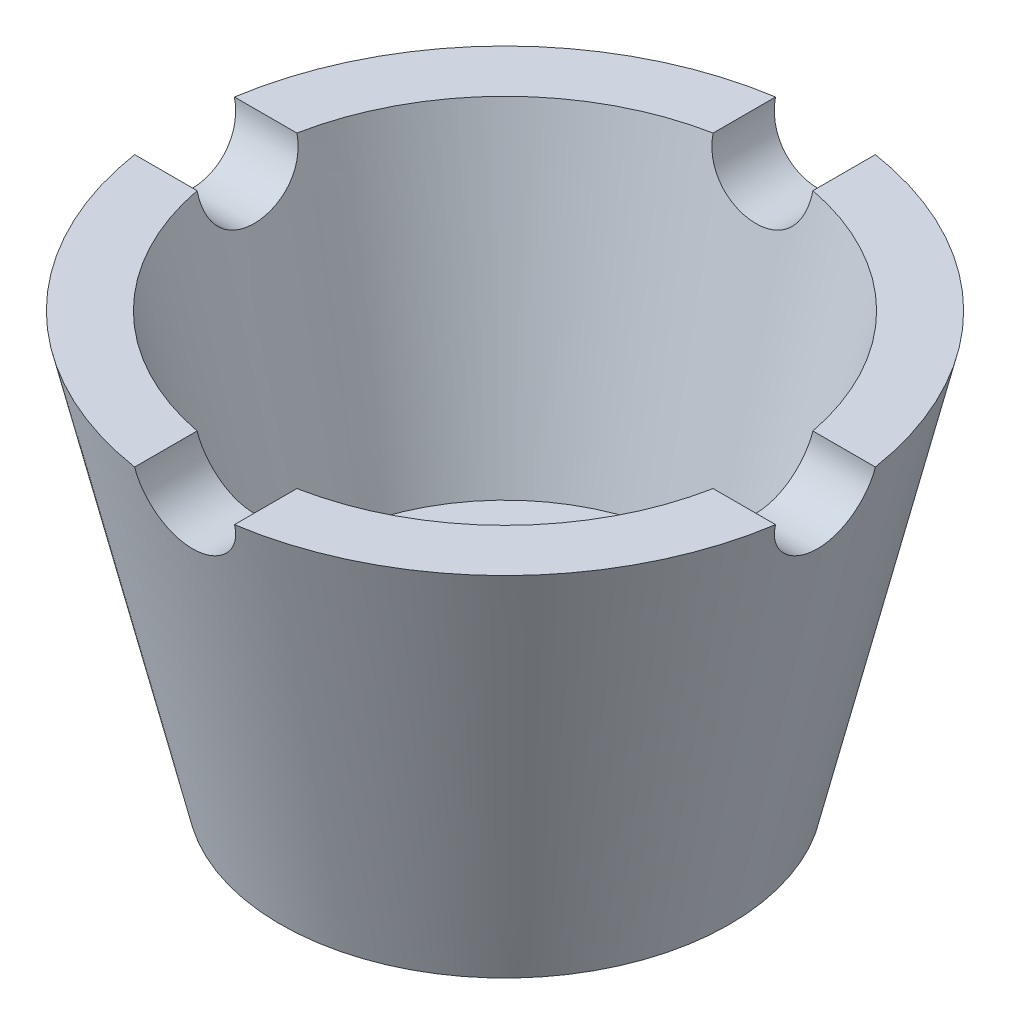
SolidWorks part; units mm, degrees
material "Cast Alloy Steel"
ref_plane "Front Plane" through (0, 0, 0) normal (0, 0, 1) x (1, 0, 0)
ref_plane "Top Plane" through (0, 0, 0) normal (0, 1, 0) x (1, 0, 0)
ref_plane "Right Plane" through (0, 0, 0) normal (1, 0, 0) x (0, 0, -1)
sketch "Sketch2" plane through (0, 0, 0) normal (0, 0, 1) x (1, 0, 0)
  line L0 (11.25, 0) -> (22.5, 0)
  line L1 (22.5, 0) -> (32.5, 42)
  line L2 (32.5, 42) -> (26.3323, 42)
  line L4 (19.1894, 12) -> (11.25, 12)
  line L5 (11.25, 12) -> (11.25, 0)
  line L6 (19.1894, 12) -> (26.3323, 42)
  line L7 (0, 0) -> (0, 42) construction
  line L8 (16.6632, 1.3897) -> (26.6632, 43.3897) construction
  dimension "D1" = 11.25
  dimension "D4" = 22.5
  dimension "D5" = 32.5
  dimension "D6" = 6
  dimension "D7" = 42
revolve "Revolve1" add sketch "Sketch2" angle 360 about L7
sketch "Sketch3" plane through (0, 0, 0) normal (1, 0, 0) x (0, 0, -1)
  line L0 (32.5, 42) -> (-32.5, 42) construction
  circle A0 centre (0, 42) radius 5
  dimension "D1" = 10
extrude "Cut-Extrude1" cut sketch "Sketch3" against normal through all both and the other way through all
sketch "Sketch4" plane through (0, 0, 0) normal (0, 0, 1) x (1, 0, 0)
  line L0 (32.1131, 42) -> (-32.1131, 42) construction
  circle A0 centre (0, 42) radius 5
  dimension "D1" = 10
extrude "Cut-Extrude2" cut sketch "Sketch4" against normal through all both and the other way through all
